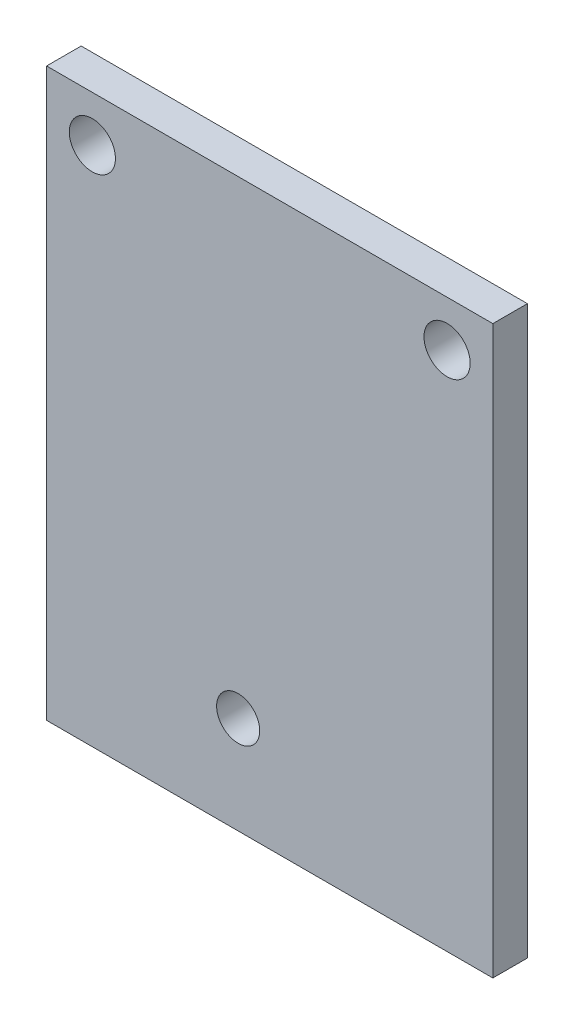
SolidWorks part; units mm, degrees
ref_plane "Front Plane" through (0, 0, 0) normal (0, 0, 1) x (1, 0, 0)
ref_plane "Top Plane" through (0, 0, 0) normal (0, 1, 0) x (1, 0, 0)
ref_plane "Right Plane" through (0, 0, 0) normal (1, 0, 0) x (0, 0, -1)
sketch "Sketch1" plane through (0, 0, 0) normal (0, 0, 1) x (1, 0, 0)
  line L0 (3, 3) -> (3, -3) construction
  line L1 (3, -3) -> (-3, -3) construction
  line L2 (-3, -3) -> (-3, 3) construction
  line L3 (-3, 3) -> (3, 3) construction
  line L4 (3, 3) -> (3, -3) construction
  line L5 (3, -3) -> (-3, -3) construction
  line L6 (-3, -3) -> (-3, 3) construction
  line L7 (-3, 3) -> (3, 3) construction
  line L9 (-10.25, 10.55) -> (9.75, 10.55)
  line L10 (-10.25, 10.55) -> (-10.25, -14.85)
  line L11 (-10.25, -14.85) -> (9.75, -14.85)
  line L12 (9.75, 10.55) -> (9.75, -14.85)
  dimension "D1" = 20
  dimension "D2" = 25.4
  dimension "D3" = 6.75
  dimension "D4" = 7.55
extrude "Boss-Extrude1" add sketch "Sketch1" along normal blind 1.5494
sketch "Sketch2" plane through (0, 0, 0) normal (0, 0, -1) x (-1, 0, 0)
  line L0 (-9.75, 10.55) -> (10.25, 10.55) construction
  line L1 (-9.75, -14.85) -> (-9.75, 10.55) construction
  line L2 (10.25, 10.55) -> (10.25, -14.85) construction
  line L3 (10.25, 10.55) -> (10.25, -14.85) construction
  circle A2 centre (8.199, 8.4989) radius 1.035
  circle A3 centre (-7.699, 8.4989) radius 1.035
  circle A4 centre (1.6648, -10.4812) radius 0.9652
  point P4 (-1.4905, -10.4812)
  dimension "D1" = 2.0701
  dimension "D2" = 2.0511
  dimension "D3" = 2.0511
  dimension "D4" = 2.0511
  dimension "D5" = 1.9304
  dimension "D6" = 8.5852
  dimension "D7" = 21.0312
extrude "Cut-Extrude1" cut sketch "Sketch2" against normal through all
